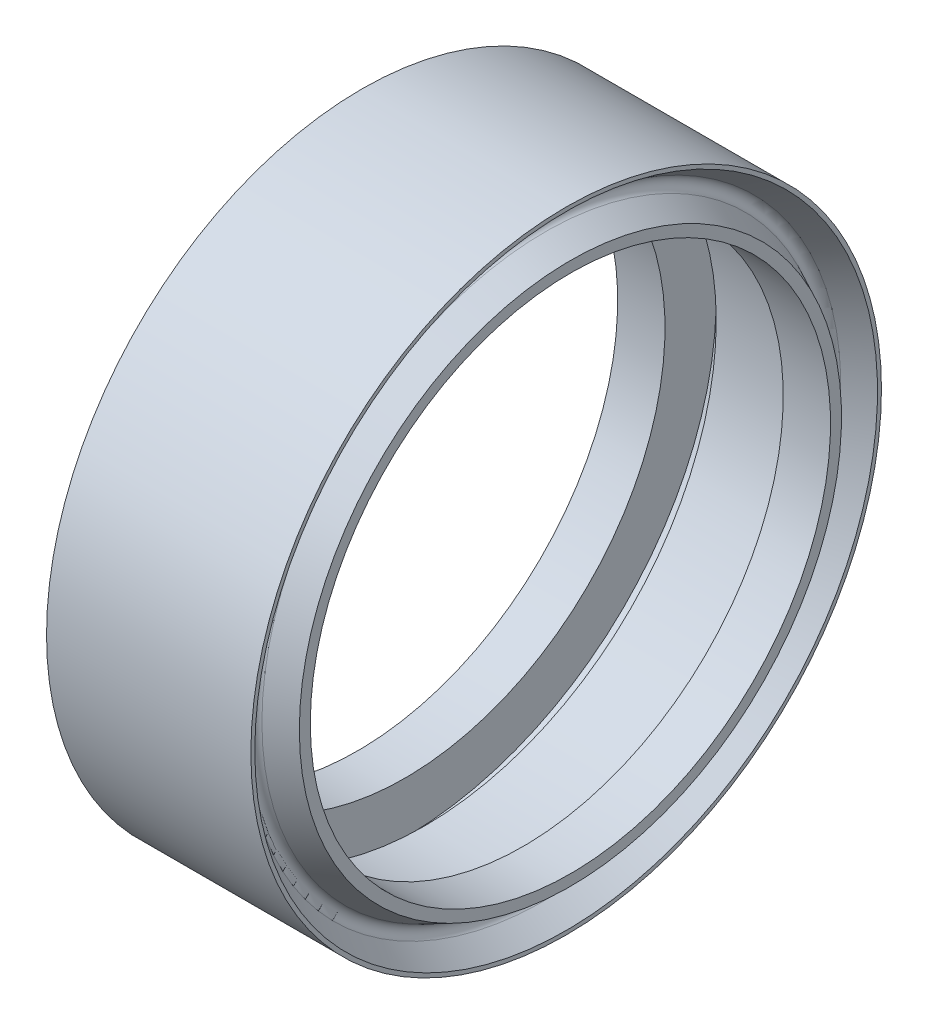
SolidWorks part; units mm, degrees
ref_plane "Alzado" through (0, 0, 0) normal (0, 0, 1) x (1, 0, 0)
ref_plane "Planta" through (0, 0, 0) normal (0, 1, 0) x (1, 0, 0)
ref_plane "Vista lateral" through (0, 0, 0) normal (1, 0, 0) x (0, 0, -1)
sketch "Croquis1" plane through (0, 0, 0) normal (0, 0, 1) x (1, 0, 0)
  line L0 (10.8461, 34.3894) -> (14.0687, 35.9136)
  line L1 (14.191, 37.6529) -> (11.385, 39.5)
  line L2 (11.385, 39.5) -> (11.385, 40)
  line L3 (11.385, 40) -> (37.3072, 40)
  line L4 (0, 0) -> (52.6356, 0) construction
  line L5 (29.3461, 37) -> (19.3461, 37)
  line L6 (19.3461, 39.5) -> (16.8461, 39.5)
  line L7 (16.8461, 39.5) -> (16.8461, 33)
  line L8 (16.8461, 33) -> (10.8461, 33)
  line L9 (10.8461, 33) -> (10.8461, 34.3894)
  line L10 (19.3461, 37) -> (19.3461, 39.5)
  line L11 (29.3461, 37) -> (29.3461, 39.5)
  line L12 (37.8461, 33) -> (37.8461, 34.3894)
  line L13 (31.8461, 33) -> (37.8461, 33)
  line L14 (31.8461, 39.5) -> (31.8461, 33)
  line L15 (29.3461, 39.5) -> (31.8461, 39.5)
  line L16 (37.3072, 39.5) -> (37.3072, 40)
  line L17 (34.5012, 37.6529) -> (37.3072, 39.5)
  line L18 (37.8461, 34.3894) -> (34.6235, 35.9136)
  arc A0 (14.191, 37.6529) -> (14.0687, 35.9136) centre (13.6411, 36.8176) cw
  arc A1 (34.5012, 37.6529) -> (34.6235, 35.9136) centre (35.0511, 36.8176) ccw
revolve "Revolución1" add sketch "Croquis1" angle 360 about L4
